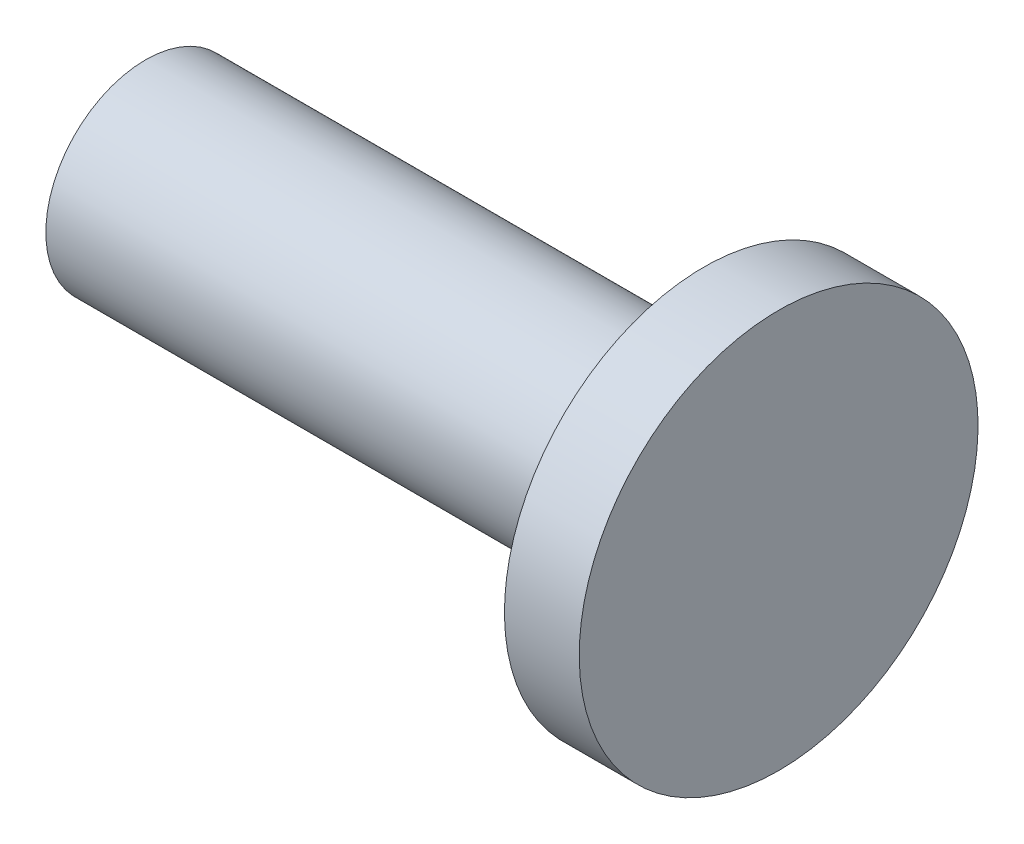
SolidWorks part; units mm, degrees
ref_plane "Front Plane" through (0, 0, 0) normal (0, 0, 1) x (1, 0, 0)
ref_plane "Top Plane" through (0, 0, 0) normal (0, 1, 0) x (1, 0, 0)
ref_plane "Right Plane" through (0, 0, 0) normal (1, 0, 0) x (0, 0, -1)
sketch "Sketch1" plane through (0, 0, 0) normal (0, 0, 1) x (1, 0, 0)
  line L0 (-41.9968, 0) -> (41.9968, 0) construction
  line L1 (0, -32.6256) -> (0, 32.6256) construction
sketch "Sketch2" plane through (0, 0, 0) normal (0, 0, 1) x (1, 0, 0)
  line L0 (-56, 10) -> (0, 10)
  line L1 (0, 10) -> (0, 20)
  line L2 (0, 20) -> (7.5, 20)
  line L3 (7.5, 20) -> (7.5, 0)
  line L4 (7.5, 0) -> (-56, 0)
  line L5 (-56, 0) -> (-56, 10)
  line L6 (0, 10) -> (0, 0) construction
  line L7 (0, -32.6256) -> (0, 32.6256) construction
  line L9 (-72.45, 0) -> (72.45, 0) construction
  dimension "D1" = 56
  dimension "D2" = 7.5
  dimension "D3" = 40
  dimension "D4" = 20
revolve "Revolve1" add sketch "Sketch2" angle 360 about L9
